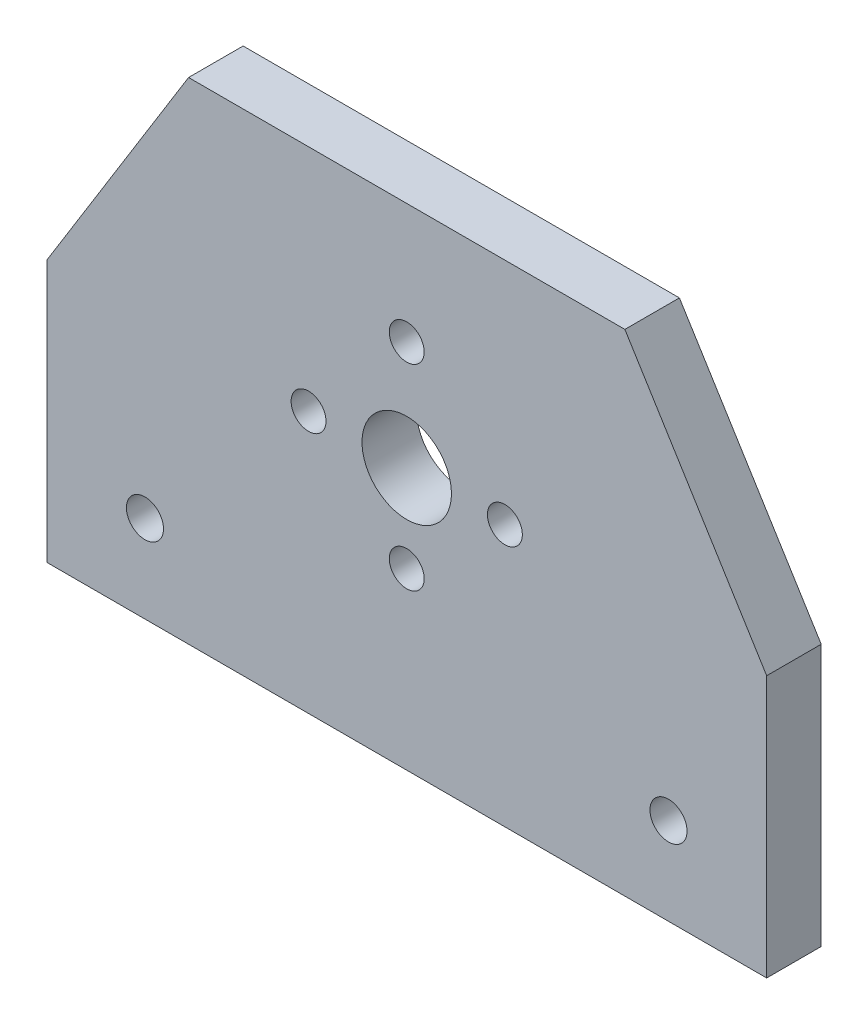
SolidWorks part; units mm, degrees
ref_plane "Спереди" through (0, 0, 0) normal (0, 0, 1) x (1, 0, 0)
ref_plane "Сверху" through (0, 0, 0) normal (0, 1, 0) x (1, 0, 0)
ref_plane "Справа" through (0, 0, 0) normal (1, 0, 0) x (0, 0, -1)
other "Configuration Table"
sketch "Эскиз1" plane through (0, 0, 0) normal (0, 0, 1) x (1, 0, 0)
  line L0 (-33, 0) -> (33, 0)
  line L1 (33, 0) -> (33, 24)
  line L2 (33, 24) -> (20, 45)
  line L3 (20, 45) -> (-20, 45)
  line L4 (-20, 45) -> (-33, 24)
  line L5 (-33, 24) -> (-33, 0)
  circle A0 centre (0, 24) radius 4.1
  circle A1 centre (-9, 24) radius 1.6
  circle A2 centre (9, 24) radius 1.6
  circle A3 centre (0, 16) radius 1.6
  circle A4 centre (0, 34) radius 1.6
  circle A5 centre (-24, 8) radius 1.7
  circle A6 centre (24, 8) radius 1.7
extrude "10_Camera_side_ear" add sketch "Эскиз1" along normal blind 5
